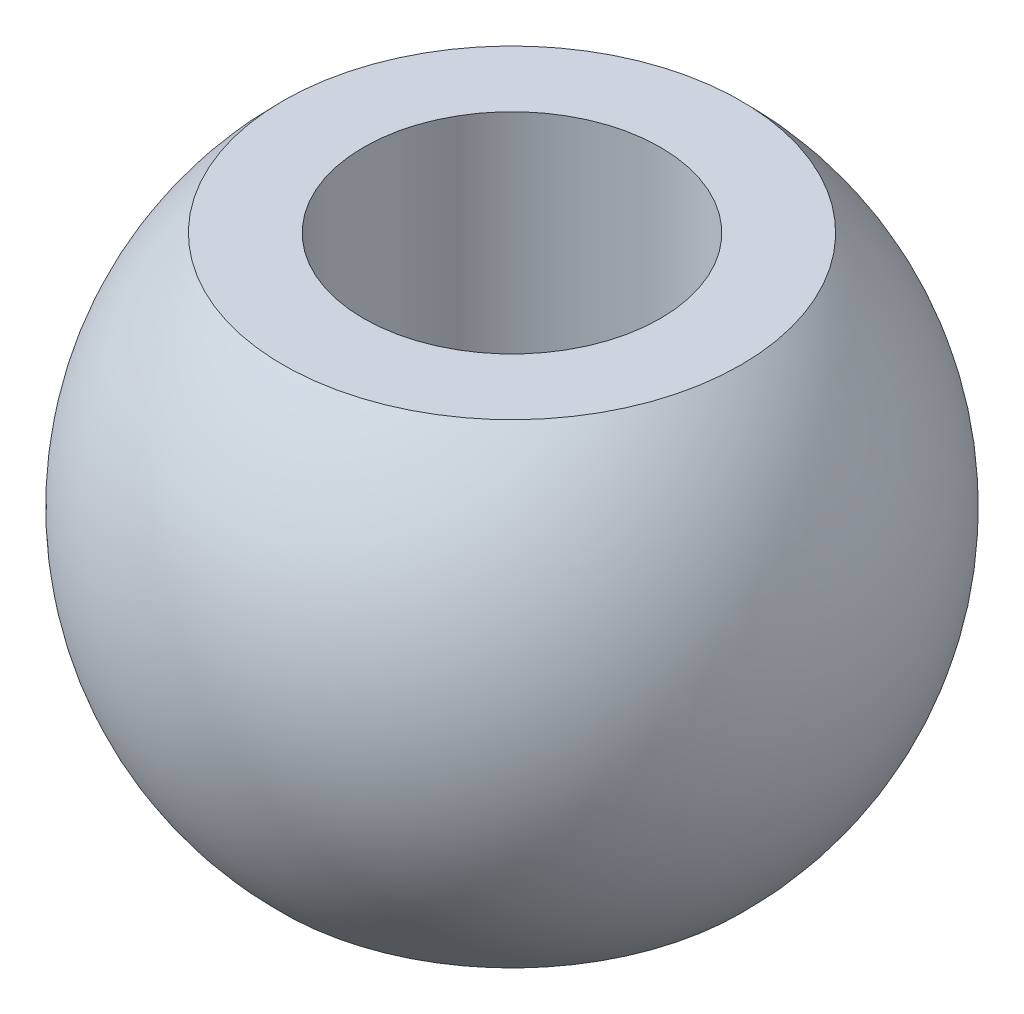
SolidWorks part; units mm, degrees
material "AISI 1010 Steel, hot rolled bar"
ref_plane "Front Plane" through (0, 0, 0) normal (0, 0, 1) x (1, 0, 0)
ref_plane "Top Plane" through (0, 0, 0) normal (0, 1, 0) x (1, 0, 0)
ref_plane "Right Plane" through (0, 0, 0) normal (1, 0, 0) x (0, 0, -1)
sketch "Sketch1" plane through (0, 0, 0) normal (0, 0, 1) x (1, 0, 0)
  line L0 (2.5, 4) -> (2.5, -4)
  line L1 (2.5, -4) -> (3.8561, -4)
  line L3 (2.5, 4) -> (3.8561, 4)
  line L5 (0, -44.7868) -> (0, 44.7868) construction
  line L6 (0, 6.85) -> (0, -9.9865) construction
  arc A1 (3.8561, -4) -> (3.8561, 4) centre (0, 0) ccw
  dimension "D1" = 8
  dimension "D2" = 5.556
  dimension "D3" = 2.5
revolve "Revolve1" add sketch "Sketch1" angle 360 about L6
